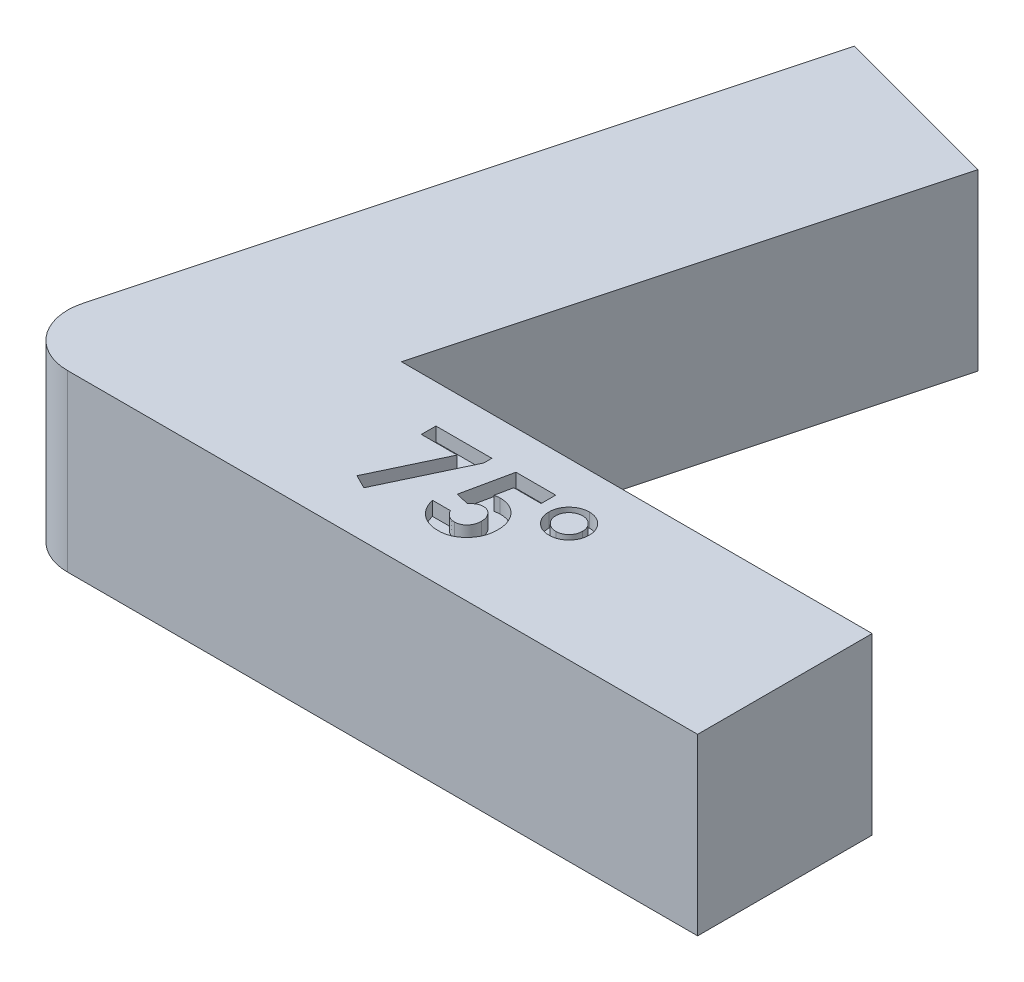
SolidWorks part; units mm, degrees
ref_plane "Front Plane" through (0, 0, 0) normal (0, 0, 1) x (1, 0, 0)
ref_plane "Top Plane" through (0, 0, 0) normal (0, 1, 0) x (1, 0, 0)
ref_plane "Right Plane" through (0, 0, 0) normal (1, 0, 0) x (0, 0, -1)
sketch "Sketch1" plane through (0, 0, 0) normal (0, 1, 0) x (1, 0, 0)
  line L0 (0, 0) -> (10.3528, 38.637)
  line L1 (0, 0) -> (40, 0)
  line L2 (13.0323, 10) -> (40, 10)
  line L3 (13.0323, 10) -> (20.012, 36.0488)
  line L4 (10.3528, 38.637) -> (20.012, 36.0488)
  line L5 (40, 10) -> (40, 0)
  dimension "D1" = 40
  dimension "D2" = 75
  dimension "D3" = 10
extrude "Boss-Extrude1" add sketch "Sketch1" along normal blind 10
sketch "Sketch2" plane through (0, 10, 0) normal (0, 1, 0) x (1, 0, 0)
  text T0 "<b>75°</b>" font "Century Gothic" height 5
extrude "Cut-Extrude1" cut sketch "Sketch2" against normal blind 0.8
fillet "Fillet1" radius 3 1 edges at (0, 5, 0)
